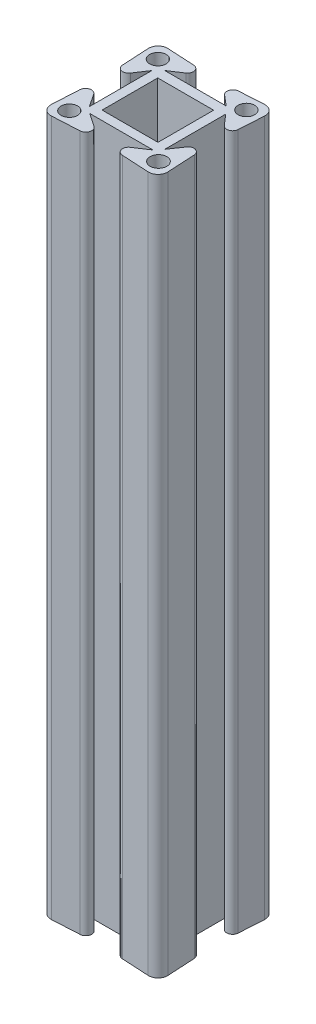
SolidWorks part; units mm, degrees
ref_plane "Front Plane" through (0, 0, 0) normal (0, 0, 1) x (1, 0, 0)
ref_plane "Top Plane" through (0, 0, 0) normal (0, 1, 0) x (1, 0, 0)
ref_plane "Right Plane" through (0, 0, 0) normal (1, 0, 0) x (0, 0, -1)
sketch "Sketch1" plane through (0, 0, 0) normal (0, 1, 0) x (1, 0, 0)
  line L1 (-16.2586, 10.8064) -> (9.1414, 10.8064)
  line L2 (-16.2586, 10.8064) -> (-16.2586, -14.5936)
  line L3 (-16.2586, -14.5936) -> (9.1414, -14.5936)
  line L4 (9.1414, 10.8064) -> (9.1414, -14.5936)
  dimension "D1" = 25.4
  dimension "D2" = 25.4
sketch "Sketch2" plane through (0, 0, 0) normal (0, 1, 0) x (1, 0, 0)
  line L0 (-19.5248, -1.8997) -> (12.956, -1.8997)
  line L1 (-3.2844, -16.3317) -> (-3.2844, 12.7118)
  line L2 (-16.2586, -14.5936) -> (9.1414, 10.8064)
  line L3 (-16.2586, 10.8064) -> (9.1414, -14.5936)
  line L4 (-16.2586, -14.5936) -> (-15.6079, -2.6453)
  line L8 (-1.665, 10.1557) -> (9.1414, 10.8064)
  line L9 (-16.2586, -14.5936) -> (-4.3104, -13.9428)
  line L10 (-4.3104, -13.9428) -> (-10.3408, -9.862)
  line L11 (-15.6079, -2.6453) -> (-11.6319, -8.6265)
  line L13 (8.4906, 0) -> (9.1414, 10.8064)
  line L16 (-4.2921, 10.1557) -> (-16.2586, 10.8064)
  line L18 (-2.8545, -13.9363) -> (9.1414, -14.5936)
  line L19 (8.4841, -2.5977) -> (4.4616, -8.4759)
  line L20 (-15.6079, -1.1601) -> (-11.6319, 4.8561)
  line L21 (-2.8545, -13.9363) -> (3.3396, -9.862)
  line L22 (-15.6079, -1.1601) -> (-16.2586, 10.8064)
  line L23 (8.4841, -2.5977) -> (9.1414, -14.5936)
  line L25 (8.4906, 0) -> (4.4616, 4.6752)
  line L26 (4.4616, -9.862) -> (-11.6319, -9.862)
  line L27 (4.4616, -9.862) -> (4.4616, 6.2316)
  line L28 (4.4616, 6.2316) -> (-11.6319, 6.2316)
  line L29 (-11.6319, -9.862) -> (-11.6319, 6.2316)
  line L30 (-1.665, 10.1557) -> (3.012, 6.2316)
  line L31 (-4.2921, 10.1557) -> (-10.2576, 6.2316)
  line L32 (3.1916, -8.592) -> (3.1916, 4.9616)
  line L33 (3.1916, 4.9616) -> (-10.3619, 4.9616)
  line L34 (-10.3619, -8.592) -> (-10.3619, 4.9616)
  line L35 (3.1916, -8.592) -> (-10.3619, -8.592)
  line L36 (4.4616, -8.4759) -> (3.3396, -9.862)
  line L37 (-10.3408, -9.862) -> (-11.6319, -8.6265)
  line L38 (4.4616, 4.6752) -> (3.012, 6.2316)
  line L39 (-10.2576, 6.2316) -> (-11.6319, 4.8561)
  dimension "D1" = 1.27
extrude "Boss-Extrude1" add sketch "Sketch2" along normal blind 150
fillet "Fillet1" radius 2.032 4 edges at (9.1414, 75, 14.5936) (9.1414, 75, -10.8064) (-16.2586, 75, -10.8064) (-16.2586, 75, 14.5936)
fillet "Fillet2" radius 1.27 8 edges at (-15.6079, 75, 2.6453) (-15.6079, 75, 1.1601) (-4.3104, 75, 13.9428) (-4.2921, 75, -10.1557) (-1.665, 75, -10.1557) (8.4906, 75, 0) (8.4841, 75, 2.5977) (-2.8545, 75, 13.9363)
sketch "Sketch5" plane through (0, 150, 0) normal (0, 1, 0) x (1, 0, 0)
  line L1 (2.4309, 4.0973) -> (-9.6178, 4.0973)
  line L2 (2.4309, 4.0973) -> (2.4309, -7.8996)
  line L3 (2.4309, -7.8996) -> (-9.6178, -7.8996)
  line L4 (-9.6178, 4.0973) -> (-9.6178, -7.8996)
  circle A0 centre (5.9214, 7.6654) radius 1.7848
  circle A1 centre (6.0507, -11.416) radius 1.8099
  circle A2 centre (-13.1083, 7.6137) radius 1.778
  circle A3 centre (-13.0307, -11.5453) radius 1.778
extrude "Cut-Extrude3" cut sketch "Sketch5" against normal through all contours L1 L4 L3 L2 | A1 | A3 | A2 | A0
scale "Scale1" bodies to scale 124 scale about centroid uniform scaling yes scale factor 0.8
